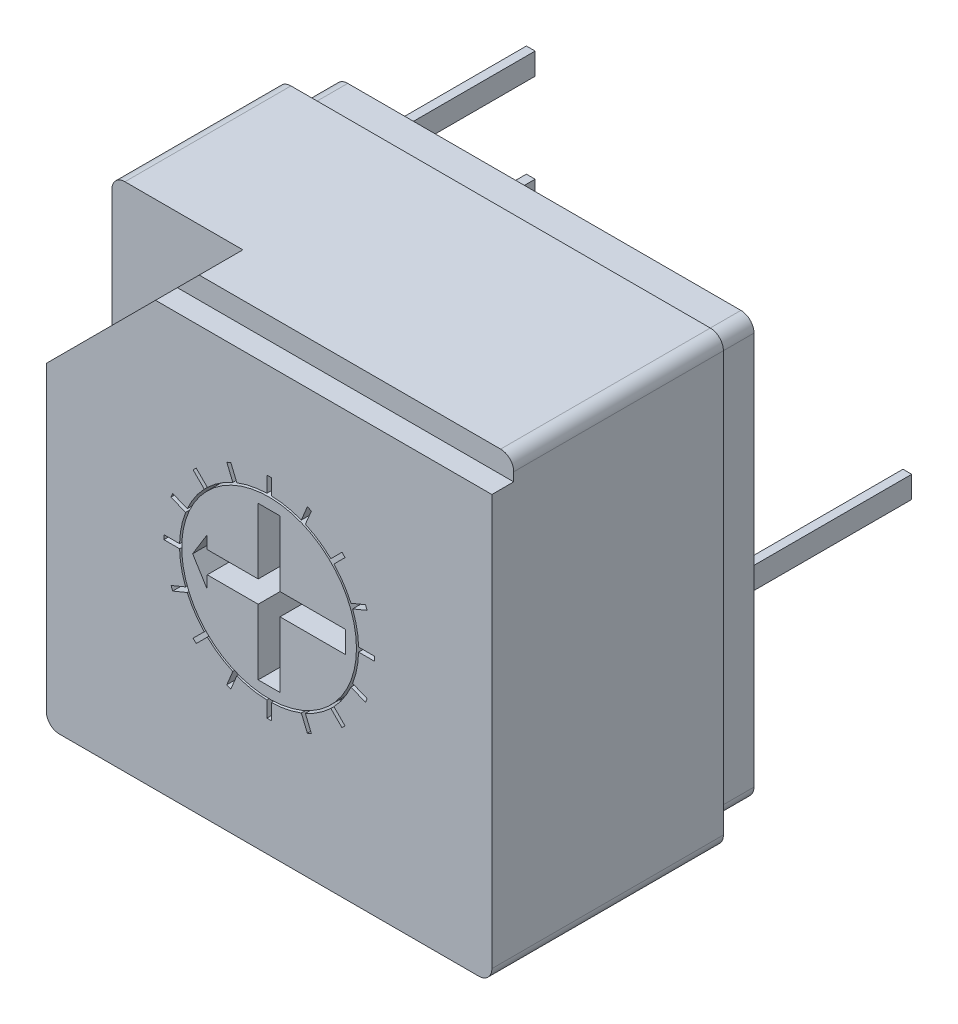
SolidWorks part; units mm, degrees
ref_plane "Front Plane" through (0, 0, 0) normal (0, 0, 1) x (1, 0, 0)
ref_plane "Top Plane" through (0, 0, 0) normal (0, 1, 0) x (1, 0, 0)
ref_plane "Right Plane" through (0, 0, 0) normal (1, 0, 0) x (0, 0, -1)
sketch "Sketch1" plane through (0, 0, 0) normal (0, 0, 1) x (1, 0, 0)
  line L1 (0, 0) -> (10.2, 0)
  line L2 (0, 0) -> (0, 10.2)
  line L3 (0, 10.2) -> (10.2, 10.2)
  line L4 (10.2, 0) -> (10.2, 10.2)
  dimension "D1" = 10.2
  dimension "D2" = 10.2
extrude "Boss-Extrude2" add sketch "Sketch1" along normal blind 6.5
sketch "Sketch3" plane through (0, 0, 0) normal (0, 0, -1) x (-1, 0, 0)
  line L0 (-8.2, 10.2) -> (-8.2, 8.2) construction
  line L1 (-10.2, 10.2) -> (0, 10.2) construction
  line L2 (-10.2, 0) -> (-10.2, 10.2) construction
  line L3 (-10.2, 8.2) -> (-8.2, 8.2) construction
  line L4 (-5.1, 10.2) -> (-5.1, 0) construction
  line L5 (0, 0) -> (-10.2, 0) construction
  line L6 (-10.2, 5.1) -> (0, 5.1) construction
  line L7 (0, 10.2) -> (0, 0) construction
  circle A0 centre (-8.2, 8.2) radius 0.5015
  circle A1 centre (-2, 8.2) radius 0.5015
  circle A2 centre (-8.2, 2) radius 0.5015
  circle A3 centre (-2, 2) radius 0.5015
  dimension "D1" = 2
  dimension "D2" = 2
extrude "Boss-Extrude3" add sketch "Sketch3" along normal blind 0.5
fillet "Fillet1" radius 0.3 4 edges at (10.2, 0, 3.25) (0, 0, 3.25) (0, 10.2, 3.25) (10.2, 10.2, 3.25)
sketch "Sketch4" plane through (0, 0, 0) normal (0, 0, -1) x (-1, 0, 0)
  line L8 (-9.9, 9.9) -> (-9.9, 0.3)
  line L9 (-9.9, 0.3) -> (-0.3, 0.3)
  line L10 (-0.3, 0.3) -> (-0.3, 9.9)
  line L11 (-0.3, 9.9) -> (-9.9, 9.9)
  line L12 (-9.9, 9.9) -> (-9.9, 0.3)
  line L13 (-9.9, 0.3) -> (-0.3, 0.3)
  line L14 (-0.3, 0.3) -> (-0.3, 9.9)
  line L15 (-0.3, 9.9) -> (-9.9, 9.9)
  dimension "D1" = 0.3
extrude "Cut-Extrude-Thin1" cut sketch "Sketch4" against normal blind 1 thin
fillet "Fillet2" radius 0.3 4 edges at (0.3, 9.9, 0.5) (9.9, 9.9, 0.5) (9.9, 0.3, 0.5) (0.3, 0.3, 0.5)
sketch "Sketch5" plane through (0, 0, 0) normal (0, 0, -1) x (-1, 0, 0)
  line L0 (-5.1, 9.9) -> (-5.1, 0.3) construction
  line L1 (-0.6, 9.9) -> (-9.6, 9.9) construction
  line L2 (-9.6, 0.3) -> (-0.6, 0.3) construction
  line L3 (-9.9, 5.1) -> (-0.3, 5.1) construction
  line L4 (-9.9, 9.6) -> (-9.9, 0.6) construction
  line L5 (-0.3, 0.6) -> (-0.3, 9.6) construction
  line L6 (-1.39, 9.1859) -> (-1.19, 8.6859) construction
  line L7 (-1.39, 9.1859) -> (-1.19, 9.1859)
  line L8 (-1.39, 9.1859) -> (-1.39, 8.6859)
  line L9 (-1.39, 8.6859) -> (-1.19, 8.6859)
  line L10 (-1.19, 9.1859) -> (-1.19, 8.6859)
  line L11 (-1.39, 8.6859) -> (-1.19, 9.1859) construction
  line L12 (-1.29, 8.9359) -> (-1.29, 6.3959) construction
  line L13 (-1.39, 6.6459) -> (-1.19, 6.6459)
  line L14 (-1.39, 6.6459) -> (-1.39, 6.1459)
  line L15 (-1.39, 6.6459) -> (-1.19, 6.1459) construction
  line L16 (-1.19, 6.6459) -> (-1.19, 6.1459)
  line L17 (-1.39, 6.1459) -> (-1.19, 6.6459) construction
  line L18 (-1.39, 6.1459) -> (-1.19, 6.1459)
  line L19 (-1.29, 6.37) -> (-1.29, 3.83) construction
  line L20 (-1.39, 3.6059) -> (-1.19, 4.1059) construction
  line L21 (-1.39, 3.6059) -> (-1.19, 3.6059)
  line L22 (-1.39, 4.1059) -> (-1.19, 3.6059) construction
  line L23 (-1.39, 4.1059) -> (-1.39, 3.6059)
  line L24 (-1.29, 3.8559) -> (-1.29, 1.3159) construction
  line L25 (-1.19, 4.1059) -> (-1.19, 3.6059)
  line L26 (-1.39, 4.1059) -> (-1.19, 4.1059)
  line L27 (-1.39, 1.5659) -> (-1.39, 1.0659)
  line L28 (-1.19, 1.5659) -> (-1.19, 1.0659)
  line L29 (-1.29, 3.83) -> (-8.91, 3.83) construction
  line L30 (-1.39, 1.5659) -> (-1.19, 1.0659) construction
  line L31 (-1.39, 1.5659) -> (-1.19, 1.5659)
  line L32 (-1.39, 1.0659) -> (-1.19, 1.0659)
  line L33 (-1.39, 1.0659) -> (-1.19, 1.5659) construction
  line L34 (-9.01, 4.1059) -> (-9.01, 3.6059)
  line L35 (-9.01, 3.6059) -> (-8.81, 4.1059) construction
  line L36 (-9.01, 3.6059) -> (-8.81, 3.6059)
  line L37 (-9.01, 4.1059) -> (-8.81, 4.1059)
  line L38 (-9.01, 4.1059) -> (-8.81, 3.6059) construction
  line L39 (-8.81, 4.1059) -> (-8.81, 3.6059)
  point P39 (-1.29, 5.1)
  dimension "D1" = 0.2
  dimension "D2" = 0.5
  dimension "D3" = 2.54
  dimension "D4" = 0.2
  dimension "D5" = 7.62
extrude "Boss-Extrude5" add sketch "Sketch5" along normal blind 3.5
sketch "Sketch6" plane through (0, 0, -3.5) normal (0, 0, -1) x (-1, 0, 0)
  line L1 (-9.01, 4.1059) -> (-8.81, 4.1059)
  line L2 (-9.01, 4.1059) -> (-9.01, 3.6059)
  line L3 (-9.01, 3.6059) -> (-8.81, 3.6059)
  line L4 (-8.81, 4.1059) -> (-8.81, 3.6059)
extrude "Boss-Extrude6" add sketch "Sketch6" along normal blind 1
sketch "Sketch7" plane through (0, 0, 6.5) normal (0, 0, 1) x (1, 0, 0)
  line L1 (0, 0) -> (10.2, 0)
  line L2 (0, 0) -> (0, 10.2)
  line L3 (0, 10.2) -> (10.2, 10.2)
  line L4 (10.2, 0) -> (10.2, 10.2)
extrude "Cut-Extrude3" cut sketch "Sketch7" against normal blind 0.2
sketch "Sketch8" plane through (0, 0, 6.3) normal (0, 0, 1) x (1, 0, 0)
  line L0 (0.8026, 10.2) -> (-0.6547, 10.2) construction
  line L1 (9.9, 10.2) -> (0.3, 10.2) construction
  line L2 (0, 9.5344) -> (0, 10.5608) construction
  line L3 (0, 0.3) -> (0, 9.9) construction
  line L4 (0, 10.2) -> (0, 7.2)
  line L5 (0, 10.2) -> (3, 10.2)
  line L6 (3, 10.2) -> (0, 7.2)
  dimension "D1" = 3
  dimension "D2" = 3
extrude "Cut-Extrude4" cut sketch "Sketch8" against normal blind 1.5
sketch "Sketch9" plane through (0, 0, 6.3) normal (0, 0, 1) x (1, 0, 0)
  line L0 (3, 10.2) -> (10.2, 10.2)
  line L1 (10.2, 10.2) -> (10.2, 9.7)
  line L2 (10.2, 0.3) -> (10.2, 9.9) construction
  line L3 (10.2, 9.7) -> (2.5, 9.7)
  line L4 (0, 7.2) -> (3, 10.2) construction
  line L5 (2.5, 9.7) -> (3, 10.2)
  dimension "D1" = 0.5
extrude "Cut-Extrude5" cut sketch "Sketch9" against normal blind 0.5
sketch "Sketch10" plane through (0, 0, 6.3) normal (0, 0, 1) x (1, 0, 0)
  line L0 (5.1, 10.2) -> (5.1, 0) construction
  line L5 (0, 5.1) -> (10.2, 5.1) construction
  circle A0 centre (5.1, 5.1) radius 2
  circle A1 centre (5.1, 5.1) radius 2.05
  dimension "D1" = 4
  dimension "D2" = 4.1
extrude "Cut-Extrude6" cut sketch "Sketch10" against normal blind 0.5
sketch "Sketch11" plane through (0, 0, 6.3) normal (0, 0, 1) x (1, 0, 0)
  line L0 (5.1, 7.1) -> (5.1, 3.1) construction
  line L1 (3.1, 5.1) -> (7.1, 5.1) construction
  line L3 (5.35, 6.85) -> (5.35, 5.35)
  line L4 (5.35, 5.35) -> (6.85, 5.35)
  line L5 (6.85, 5.35) -> (6.85, 4.85)
  line L6 (6.85, 4.85) -> (5.35, 4.85)
  line L7 (5.35, 4.85) -> (5.35, 3.35)
  line L8 (5.35, 3.35) -> (4.85, 3.35)
  line L9 (4.85, 3.35) -> (4.85, 4.85)
  line L10 (4.85, 4.85) -> (3.6839, 4.85)
  line L11 (3.6839, 4.85) -> (3.6839, 4.5617)
  line L12 (3.6839, 4.5617) -> (3.35, 5.1)
  line L13 (3.35, 5.1) -> (3.6839, 5.6451)
  line L14 (3.6839, 5.6451) -> (3.6839, 5.35)
  line L15 (3.6839, 5.35) -> (4.85, 5.35)
  line L16 (4.85, 5.35) -> (4.85, 6.85)
  line L17 (4.85, 6.85) -> (5.35, 6.85)
  circle A0 centre (5.1, 5.1) radius 2 construction
  dimension "D1" = 0.5
  dimension "D2" = 0.5
  dimension "D3" = 0.5
  dimension "D4" = 0.5
  dimension "D5" = 1.5
  dimension "D6" = 1.5
  dimension "D7" = 1.5
  dimension "D8" = 1.5
extrude "Cut-Extrude7" cut sketch "Sketch11" against normal blind 1
sketch "Sketch12" plane through (0, 0, 6.3) normal (0, 0, 1) x (1, 0, 0)
  line L0 (5.1, 10.1079) -> (5.1, 0.0921) construction
  line L5 (0.0381, 5.1) -> (10.2381, 5.1) construction
  line L6 (2.6247, 7.5753) -> (7.609, 2.591) construction
  line L7 (1.6368, 6.5345) -> (8.2615, 3.7905) construction
  line L8 (6.6032, 8.7291) -> (3.959, 2.3453) construction
  line L9 (7.7672, 7.7672) -> (2.515, 2.515) construction
  line L10 (3.7601, 8.3347) -> (6.5394, 1.6249) construction
  line L11 (8.9205, 6.6825) -> (1.6869, 3.6862) construction
  line L12 (5.05, 7.5091) -> (5.15, 7.5091)
  line L13 (5.15, 7.5091) -> (5.15, 7.1494)
  line L14 (5.05, 7.5091) -> (5.05, 7.1494)
  line L15 (5.1, 5.1) -> (4.4953, 8.1399) construction
  line L17 (4.2243, 7.3449) -> (4.1319, 7.3066)
  line L18 (4.2243, 7.3449) -> (4.3619, 7.0125)
  line L19 (4.1319, 7.3066) -> (4.2695, 6.9743)
  line L20 (2.8551, 5.9757) -> (3.1875, 5.8381)
  line L21 (2.8934, 6.0681) -> (3.2257, 5.9305)
  line L22 (2.8551, 5.9757) -> (2.8934, 6.0681)
  line L23 (2.6909, 5.15) -> (2.6909, 5.05)
  line L24 (2.6909, 5.15) -> (3.0506, 5.15)
  line L25 (2.6909, 5.05) -> (3.0506, 5.05)
  line L26 (3.4319, 6.8389) -> (3.3611, 6.7681)
  line L27 (3.4319, 6.8389) -> (3.6862, 6.5845)
  line L28 (3.3611, 6.7681) -> (3.6155, 6.5138)
  line L29 (3.4319, 3.3611) -> (3.6862, 3.6155)
  line L30 (3.3611, 3.4319) -> (3.6155, 3.6862)
  line L31 (3.4319, 3.3611) -> (3.3611, 3.4319)
  line L32 (4.1319, 2.8934) -> (4.2243, 2.8551)
  line L33 (4.2243, 2.8551) -> (4.3619, 3.1875)
  line L34 (4.1319, 2.8934) -> (4.2695, 3.2257)
  line L35 (5.15, 2.6909) -> (5.15, 3.0506)
  line L36 (5.05, 2.6909) -> (5.05, 3.0506)
  line L37 (5.15, 2.6909) -> (5.05, 2.6909)
  line L38 (6.0681, 2.8934) -> (5.9305, 3.2257)
  line L39 (5.9757, 2.8551) -> (5.8381, 3.1875)
  line L40 (6.0681, 2.8934) -> (5.9757, 2.8551)
  line L41 (6.7681, 3.3611) -> (6.8389, 3.4319)
  line L42 (6.7681, 3.3611) -> (6.5138, 3.6155)
  line L43 (6.8389, 3.4319) -> (6.5845, 3.6862)
  line L44 (2.8551, 4.2243) -> (2.8934, 4.1319)
  line L45 (2.8934, 4.1319) -> (3.2257, 4.2695)
  line L46 (2.8551, 4.2243) -> (3.1875, 4.3619)
  line L47 (7.3449, 4.2243) -> (7.0125, 4.3619)
  line L48 (7.3066, 4.1319) -> (6.9743, 4.2695)
  line L49 (7.3449, 4.2243) -> (7.3066, 4.1319)
  line L50 (7.5091, 5.15) -> (7.1494, 5.15)
  line L51 (7.5091, 5.05) -> (7.1494, 5.05)
  line L52 (7.5091, 5.15) -> (7.5091, 5.05)
  line L53 (7.3449, 5.9757) -> (7.3066, 6.0681)
  line L54 (7.3066, 6.0681) -> (6.9743, 5.9305)
  line L55 (7.3449, 5.9757) -> (7.0125, 5.8381)
  line L56 (6.7681, 6.8389) -> (6.5138, 6.5845)
  line L57 (6.8389, 6.7681) -> (6.5845, 6.5138)
  line L58 (6.7681, 6.8389) -> (6.8389, 6.7681)
  line L59 (5.9757, 7.3449) -> (5.8381, 7.0125)
  line L60 (6.0681, 7.3066) -> (5.9305, 6.9743)
  line L61 (5.9757, 7.3449) -> (6.0681, 7.3066)
  circle A0 centre (5.1, 5.1) radius 2.05 construction
  circle A1 centre (5.1, 5.1) radius 2.05 construction
  arc A2 (5.05, 7.1494) -> (5.15, 7.1494) centre (5.1, 5.1) cw
  arc A3 (4.3619, 7.0125) -> (4.2695, 6.9743) centre (5.1, 5.1) ccw
  arc A4 (3.1875, 5.8381) -> (3.2257, 5.9305) centre (5.1, 5.1) cw
  arc A5 (3.0506, 5.15) -> (3.0506, 5.05) centre (5.1, 5.1) ccw
  arc A6 (3.6862, 6.5845) -> (3.6155, 6.5138) centre (5.1, 5.1) ccw
  arc A7 (3.6862, 3.6155) -> (3.6155, 3.6862) centre (5.1, 5.1) cw
  arc A8 (4.2695, 3.2257) -> (4.3619, 3.1875) centre (5.1, 5.1) ccw
  arc A9 (5.15, 3.0506) -> (5.05, 3.0506) centre (5.1, 5.1) cw
  arc A10 (5.9305, 3.2257) -> (5.8381, 3.1875) centre (5.1, 5.1) cw
  arc A11 (6.5138, 3.6155) -> (6.5845, 3.6862) centre (5.1, 5.1) ccw
  arc A12 (3.1875, 4.3619) -> (3.2257, 4.2695) centre (5.1, 5.1) ccw
  arc A13 (7.0125, 4.3619) -> (6.9743, 4.2695) centre (5.1, 5.1) cw
  arc A14 (7.1494, 5.15) -> (7.1494, 5.05) centre (5.1, 5.1) cw
  arc A15 (7.0125, 5.8381) -> (6.9743, 5.9305) centre (5.1, 5.1) ccw
  arc A16 (6.5138, 6.5845) -> (6.5845, 6.5138) centre (5.1, 5.1) cw
  arc A17 (5.8381, 7.0125) -> (5.9305, 6.9743) centre (5.1, 5.1) cw
  point P29 (5.1, 5.1)
  dimension "D1" = 22.5
  dimension "D2" = 22.5
  dimension "D3" = 22.5
  dimension "D4" = 0.1
  dimension "D5" = 22.5
  dimension "D6" = 22.5
  dimension "D7" = 22.5
  dimension "D8" = 11.25
extrude "Cut-Extrude8" cut sketch "Sketch12" against normal blind 0.3
